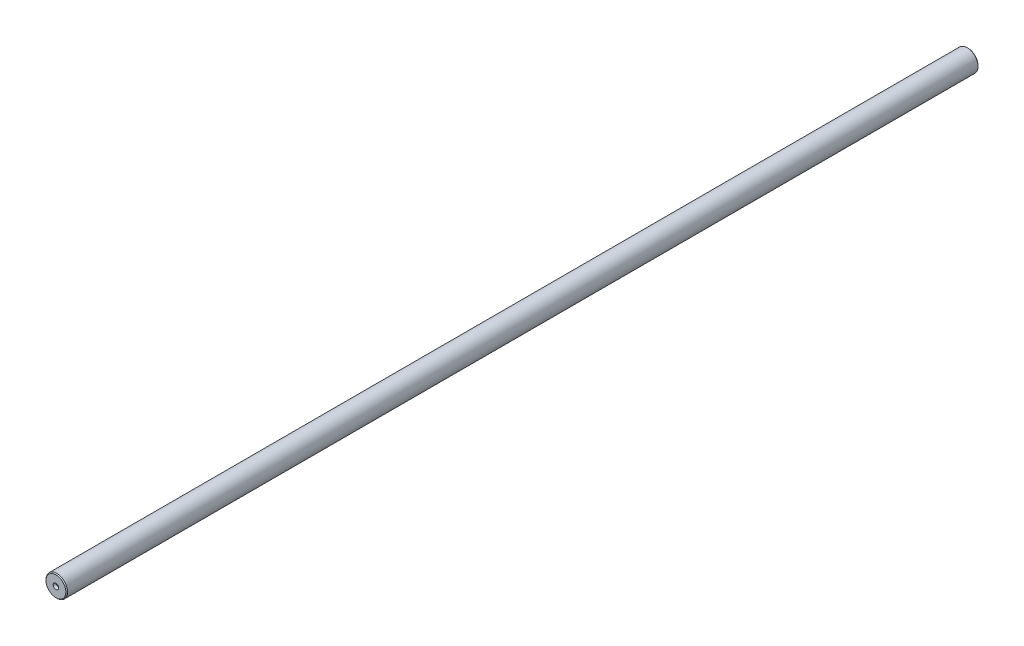
SolidWorks part; units mm, degrees
ref_plane "Front Plane" through (0, 0, 0) normal (0, 0, 1) x (1, 0, 0)
ref_plane "Top Plane" through (0, 0, 0) normal (0, 1, 0) x (1, 0, 0)
ref_plane "Right Plane" through (0, 0, 0) normal (1, 0, 0) x (0, 0, -1)
sketch "Sketch1" plane through (0, 0, 0) normal (0, 0, 1) x (1, 0, 0)
  circle A0 centre (0, 0) radius 12.5
  dimension "D1" = 25
extrude "Corpo Ø25×1056" add sketch "Sketch1" along normal mid plane 1056
cosmetic thread "Cosmetic Thread1" parameters "D2"=15
hole_wizard "Furo de Centro" positions "Sketch3" profile "Sketch4" countersink size "M3" standard "ANSI Metric"
sketch "Sketch3" plane through (0, 0, -528) normal (0, 0, -1) x (-1, 0, 0)
  point P0 (0, 0)
sketch "Sketch4" plane through (0, 0, -528) normal (1, 0, 0) x (0, 1, 0)
  line L0 (0, 0) -> (0, 10)
  line L1 (0, 10) -> (1.7, 8.9785)
  line L2 (1.7, 8.9785) -> (1.7, 2.5115)
  line L3 (1.7, 2.5115) -> (3.15, 0)
  line L5 (3.15, 0) -> (0, 0)
  line L6 (-1.7, 2.5115) -> (-3.15, 0) construction
  line L10 (0, 10) -> (-1.7, 8.9785) construction
  line L11 (0, -6.35) -> (0, 107.95) construction
  dimension "Hole Dia." = 3.4
  dimension "Hole Depth" = 10
  dimension "Near C'Sink Dia." = 6.3
  dimension "Near C'Sink Angle" = 60
  dimension "Drill Angle" = 118
mirror "Furo de Centro Espelhado" about plane through (0, 0, 0) normal (0, 0, 1) of "Furo de Centro"
chamfer "Chanfro 1×45°" distance 1 angle 45 2 edges at (12.5, 0, 528) (12.5, 0, -528)
